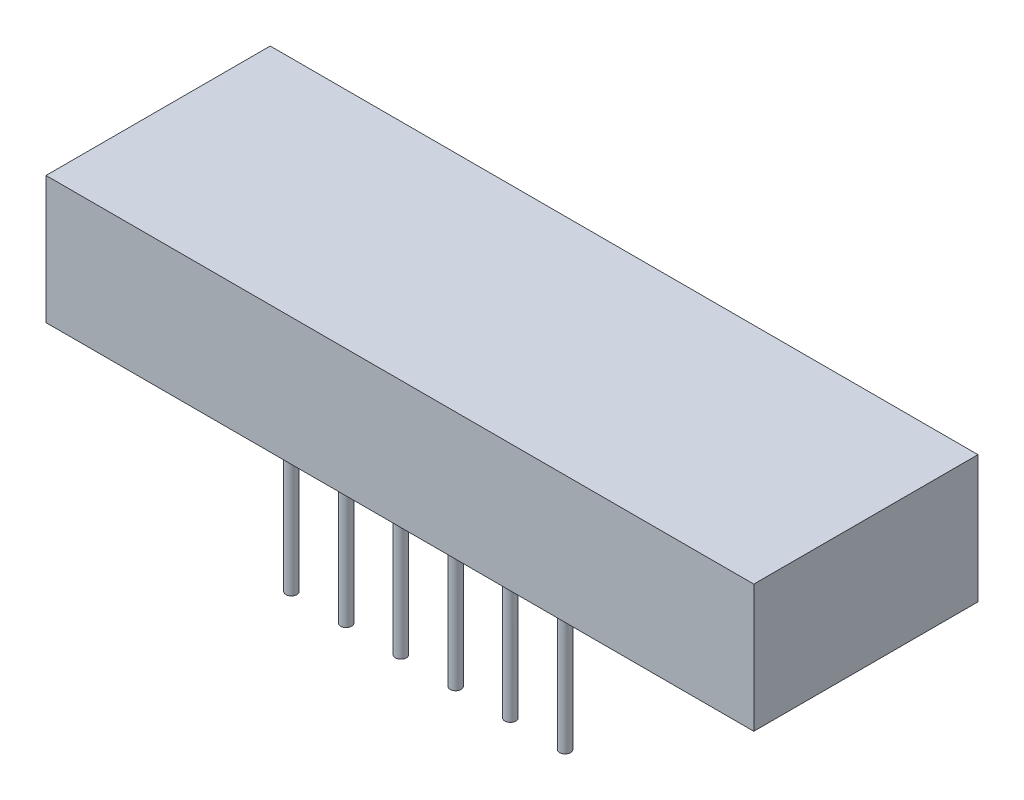
SolidWorks part; units mm, degrees
ref_plane "前视基准面" through (0, 0, 0) normal (0, 0, 1) x (1, 0, 0)
ref_plane "上视基准面" through (0, 0, 0) normal (0, 1, 0) x (1, 0, 0)
ref_plane "右视基准面" through (0, 0, 0) normal (1, 0, 0) x (0, 0, -1)
sketch "草图1" plane through (0, 0, 0) normal (0, 1, 0) x (1, 0, 0)
  line L0 (-29.3463, 0) -> (31.8739, 0) construction
  line L1 (-16.1, 5.1) -> (16.1, 5.1)
  line L2 (-16.1, 5.1) -> (-16.1, -5.1)
  line L3 (-16.1, -5.1) -> (16.1, -5.1)
  line L4 (16.1, 5.1) -> (16.1, -5.1)
  line L5 (0, 30.3794) -> (0, -29.5342) construction
  dimension "D1" = 32.2
  dimension "D2" = 10.2
extrude "拉伸1" add sketch "草图1" along normal blind 5.8
sketch "草图2" plane through (0, 0, 0) normal (0, -1, 0) x (1, 0, 0)
  line L0 (22.7617, 0) -> (-24.809, 0) construction
  line L1 (0, 10.3572) -> (0, -11.9228) construction
  line L2 (5.6198, 3.81) -> (-6.2174, 3.81) construction
  line L3 (5.6198, -3.81) -> (-6.2174, -3.81) construction
  circle A0 centre (6.2247, 3.81) radius 0.25
  circle A1 centre (3.7348, 3.81) radius 0.25
  circle A2 centre (1.2449, 3.81) radius 0.25
  circle A3 centre (-1.2449, 3.81) radius 0.25
  circle A4 centre (-3.7348, 3.81) radius 0.25
  circle A5 centre (-6.2247, 3.81) radius 0.25
  circle A6 centre (-6.2247, -3.81) radius 0.25
  circle A7 centre (-3.7348, -3.81) radius 0.25
  circle A8 centre (-1.2449, -3.81) radius 0.25
  circle A9 centre (1.2449, -3.81) radius 0.25
  circle A10 centre (3.7348, -3.81) radius 0.25
  circle A11 centre (6.2247, -3.81) radius 0.25
  dimension "D1" = 0.5
  dimension "D2" = 7.62
extrude "拉伸2" add sketch "草图2" along normal blind 6.3
